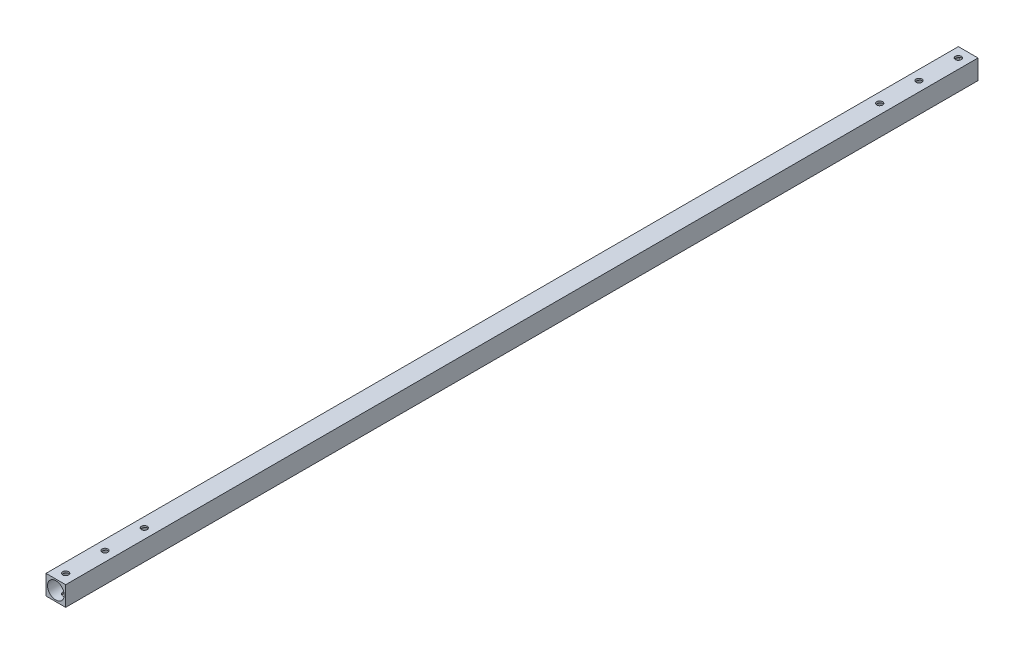
SolidWorks part; units mm, degrees
material "Thornel VCB-20 Carbon Cloth"
ref_plane "Front Plane" through (0, 0, 0) normal (0, 0, 1) x (1, 0, 0)
ref_plane "Top Plane" through (0, 0, 0) normal (0, 1, 0) x (1, 0, 0)
ref_plane "Right Plane" through (0, 0, 0) normal (1, 0, 0) x (0, 0, -1)
sketch "Sketch1" plane through (0, 0, 0) normal (0, 0, 1) x (1, 0, 0)
  line L1 (-5, -5) -> (5, -5)
  line L2 (-5, -5) -> (-5, 5)
  line L3 (-5, 5) -> (5, 5)
  line L4 (5, -5) -> (5, 5)
  line L5 (-5, -5) -> (5, 5) construction
  line L6 (-5, 5) -> (5, -5) construction
  circle A0 centre (0, 0) radius 4.25
  point P0 (0, 0)
  dimension "D3" = 8.5
  dimension "D1" = 10
  dimension "D2" = 10
extrude "Boss-Extrude1" add sketch "Sketch1" along normal blind 464
sketch "Sketch2" plane through (0, 5, 0) normal (0, 1, 0) x (1, 0, 0)
  line L0 (0, 0) -> (0, -5) construction
  line L1 (0, -5) -> (0, -25) construction
  line L2 (0, -25) -> (0, -45) construction
  line L3 (0, -464) -> (0, -459) construction
  line L4 (5, -464) -> (-5, -464) construction
  line L5 (0, -459) -> (0, -439) construction
  line L6 (0, -439) -> (0, -419) construction
  circle A0 centre (0, -5) radius 1.5
  circle A1 centre (0, -25) radius 1.5
  circle A2 centre (0, -45) radius 1.5
  circle A3 centre (0, -459) radius 1.5
  circle A4 centre (0, -439) radius 1.5
  circle A5 centre (0, -419) radius 1.5
  dimension "D3" = 3
  dimension "D4" = 5
  dimension "D6" = 3
  dimension "D1" = 5
  dimension "D2" = 20
  dimension "D5" = 20
extrude "Cut-Extrude1" cut sketch "Sketch2" against normal through all
